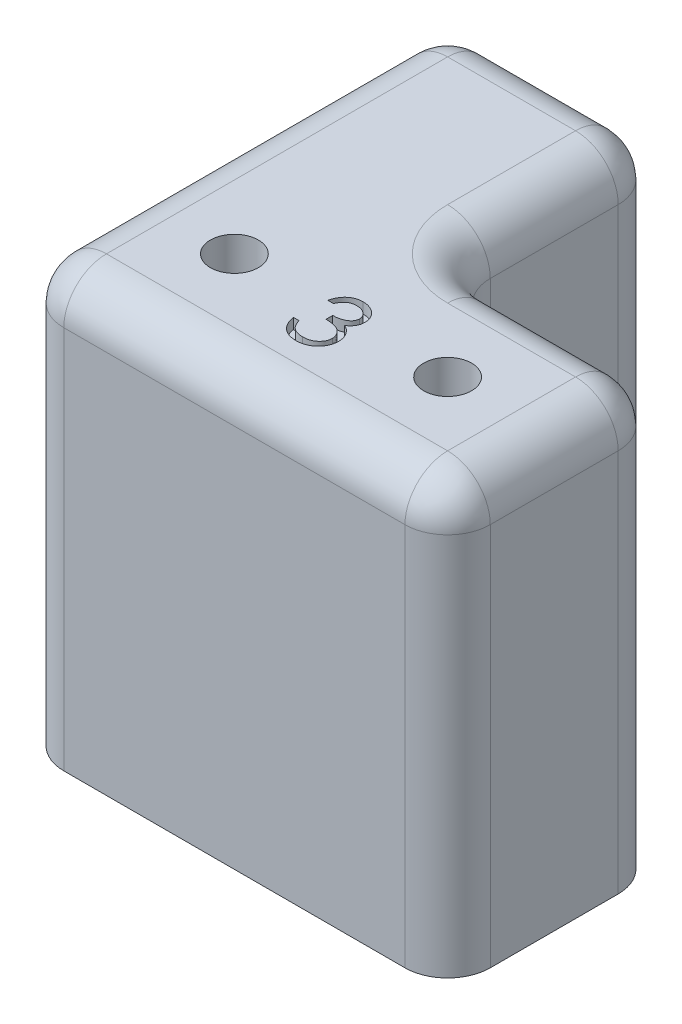
SolidWorks part; units mm, degrees
ref_plane "Alzado" through (0, 0, 0) normal (0, 0, 1) x (1, 0, 0)
ref_plane "Planta" through (0, 0, 0) normal (0, 1, 0) x (1, 0, 0)
ref_plane "Vista lateral" through (0, 0, 0) normal (1, 0, 0) x (0, 0, -1)
sketch "Croquis1" plane through (0, 0, 0) normal (0, 1, 0) x (1, 0, 0)
  line L0 (0, 0) -> (40, 0)
  line L1 (40, 0) -> (40, 20)
  line L2 (40, 20) -> (20, 20)
  line L3 (20, 20) -> (20, 40)
  line L4 (20, 40) -> (0, 40)
  line L5 (0, 40) -> (0, 0)
extrude "Saliente-Extruir1" add sketch "Croquis1" along normal blind 40
sketch "Croquis2" plane through (0, 40, 0) normal (0, 1, 0) x (1, 0, 0)
  line L0 (40, 0) -> (40, 10) construction
  line L1 (40, 0) -> (40, 20) construction
  line L2 (40, 10) -> (30, 10) construction
  line L3 (0, 0) -> (10, 0) construction
  line L4 (0, 0) -> (40, 0) construction
  line L5 (10, 0) -> (10, 10) construction
  circle A0 centre (30, 10) radius 2.25
  circle A1 centre (10, 10) radius 2.25
extrude "Cortar-Extruir1" cut sketch "Croquis2" against normal up to next
fillet "Redondeo3" radius 4 12 edges at (40, 20, 0) (0, 20, 0) (0, 20, -40) (20, 20, -40) (20, 20, -20) (40, 20, -20) (40, 40, -10) (20, 40, 0) (0, 40, -20) (10, 40, -40) (30, 40, -20) (20, 40, -30)
sketch "Croquis3" plane through (0, 0, -40) normal (0, 0, -1) x (-1, 0, 0)
  line L0 (-16, 0) -> (-10, 0) construction
  line L1 (-16, 0) -> (-4, 0) construction
  line L2 (-10, 30) -> (-10, 0) construction
  circle A0 centre (-10, 30) radius 4.15
extrude "Cortar-Extruir3" cut sketch "Croquis3" against normal blind 25
sketch "Croquis6" plane through (0, 40, 0) normal (0, 1, 0) x (1, 0, 0)
  line L0 (4, 5.9923) -> (36, 5.9923) construction
  line L1 (4, 36) -> (4, 4) construction
  line L2 (36, 4) -> (36, 16) construction
  text T0 "3" font "Century Gothic" height 6
extrude "Cortar-Extruir5" cut sketch "Croquis6" against normal blind 1
sketch "Croquis7" plane through (0, 0, 0) normal (-1, 0, 0) x (0, 0, 1)
  line L0 (-36, 0) -> (-4, 0) construction
  line L1 (-4, 0) -> (-4, 36) construction
  circle A0 centre (-26, 20) radius 2.65
  dimension "D2" = 22
  dimension "D3" = 5.3
  dimension "D1" = 20
extrude "Cortar-Extruir6" cut sketch "Croquis7" against normal through all
